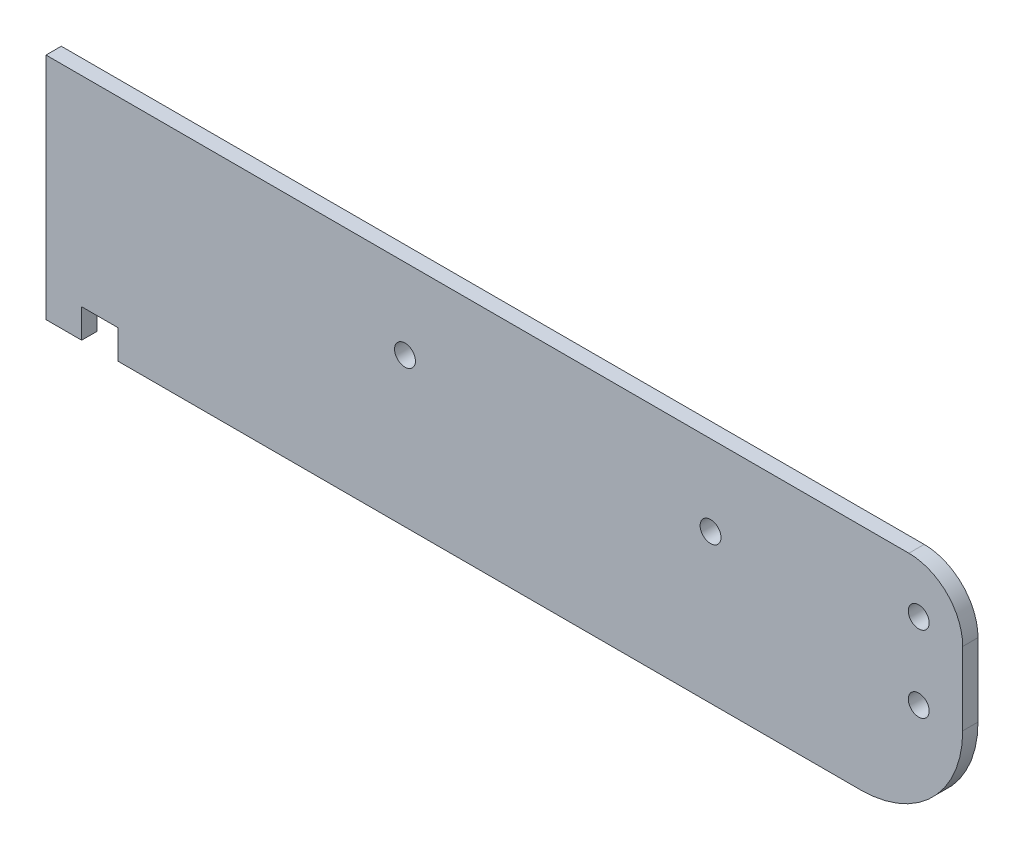
SolidWorks part; units mm, degrees
ref_plane "정면" through (0, 0, 0) normal (0, 0, 1) x (1, 0, 0)
ref_plane "윗면" through (0, 0, 0) normal (0, 1, 0) x (1, 0, 0)
ref_plane "우측면" through (0, 0, 0) normal (1, 0, 0) x (0, 0, -1)
sketch "스케치1" plane through (0, 0, 0) normal (0, 0, 1) x (1, 0, 0)
  line L1 (-57.2902, 13.3642) -> (122.7098, 13.3642)
  line L2 (-57.2902, 13.3642) -> (-57.2902, -31.6358)
  line L3 (-57.2902, -31.6358) -> (122.7098, -31.6358)
  line L4 (122.7098, 13.3642) -> (122.7098, -31.6358)
  line L5 (122.7098, 13.3642) -> (77.9625, 13.3642)
  line L6 (122.7098, 13.3642) -> (122.7098, 23.3642)
  line L7 (-57.2902, 1.6304) -> (-113.6054, 1.6304)
  line L8 (-57.2902, 1.6304) -> (-57.2902, 13.3642)
  line L9 (-57.2902, 13.3642) -> (-113.6054, 13.3642)
  line L10 (-113.6054, 1.6304) -> (-113.6054, 13.3642)
  arc A0 (122.7098, -11.5602) -> (102.6341, -31.6358) centre (102.6341, -11.5602) cw
  arc A1 (122.7098, 2.7926) -> (112.1382, 13.3642) centre (112.1382, 2.7926) ccw
  arc A2 (-65.6184, 1.6304) -> (-57.2902, -6.6977) centre (-65.6184, -6.6977) cw
  dimension "D1" = 45
  dimension "D2" = 180
extrude "보스-돌출1" add sketch "스케치1" along normal blind 3 contours A0 L4 L1 L2 L3
sketch "스케치2" plane through (0, 0, 0) normal (0, 0, -1) x (-1, 0, 0)
  line L0 (57.2902, -31.6358) -> (-102.6341, -31.6358) construction
  line L1 (50.2902, -31.6358) -> (43.1902, -31.6358)
  line L2 (50.2902, -31.6358) -> (50.2902, -25.9358)
  line L3 (50.2902, -25.9358) -> (43.1902, -25.9358)
  line L4 (43.1902, -31.6358) -> (43.1902, -25.9358)
  line L5 (57.2902, 13.3642) -> (57.2902, -31.6358) construction
  dimension "D1" = 7
  dimension "D2" = 7.1
  dimension "D3" = 5.7
extrude "컷-돌출1" cut sketch "스케치2" against normal through all
sketch "스케치3" plane through (0, 0, 0) normal (0, 0, -1) x (-1, 0, 0)
  circle A0 centre (-114.073, 3.507) radius 2.05
  circle A1 centre (-73.1986, -2.4194) radius 2.05
  circle A2 centre (-114.073, -11.493) radius 2.05
  circle A3 centre (-13.1986, -2.4194) radius 2.05
  circle A4 centre (-13.1986, -2.4194) radius 1.985 construction
  dimension "D1" = 4.1
  dimension "D2" = 4.1
  dimension "D3" = 4.1
  dimension "D5" = 4.1
  dimension "D4" = 15
extrude "컷-돌출2" cut sketch "스케치3" against normal through all
